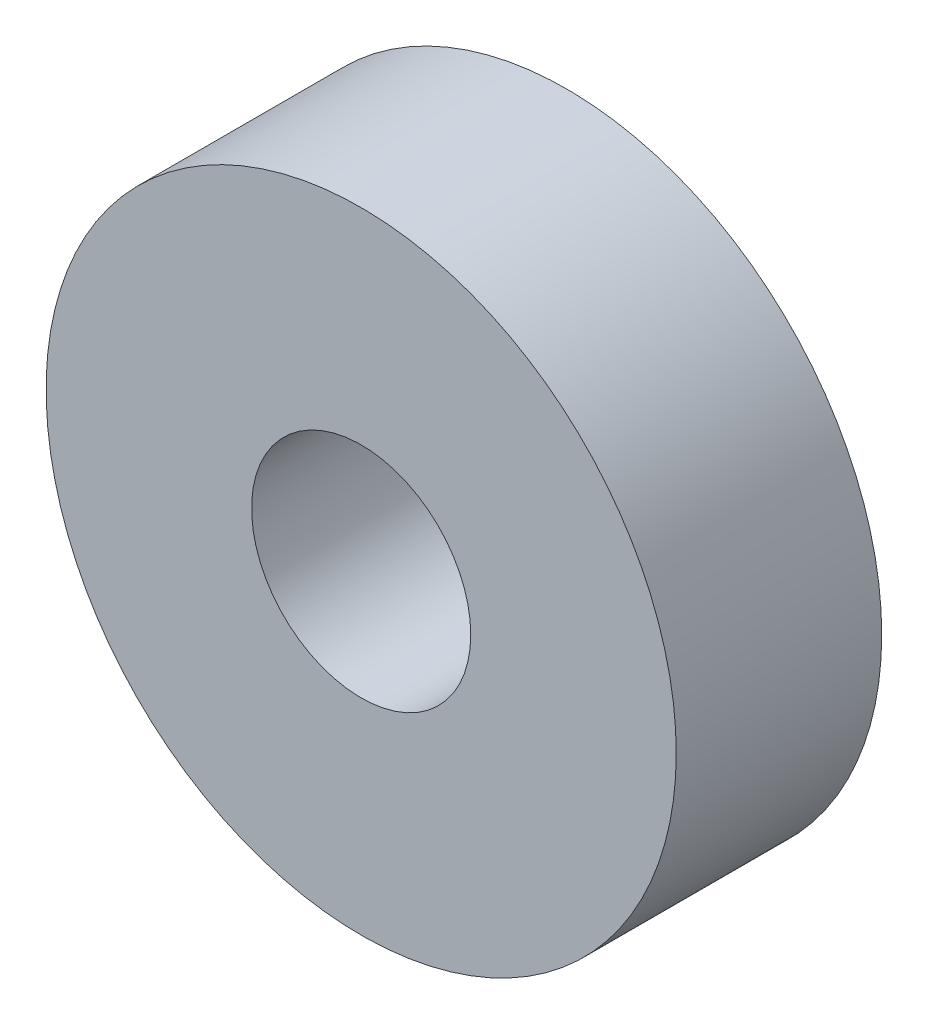
SolidWorks part; units mm, degrees
ref_plane "Front Plane" through (0, 0, 0) normal (0, 0, 1) x (1, 0, 0)
ref_plane "Top Plane" through (0, 0, 0) normal (0, 1, 0) x (1, 0, 0)
ref_plane "Right Plane" through (0, 0, 0) normal (1, 0, 0) x (0, 0, -1)
sketch "Sketch1" plane through (0, 0, 0) normal (0, 0, 1) x (1, 0, 0)
  circle A0 centre (0, 0) radius 1.6
  circle A1 centre (0, 0) radius 4.6
  dimension "D1" = 3.2
  dimension "D2" = 3
extrude "Boss-Extrude1" add sketch "Sketch1" along normal blind 3
